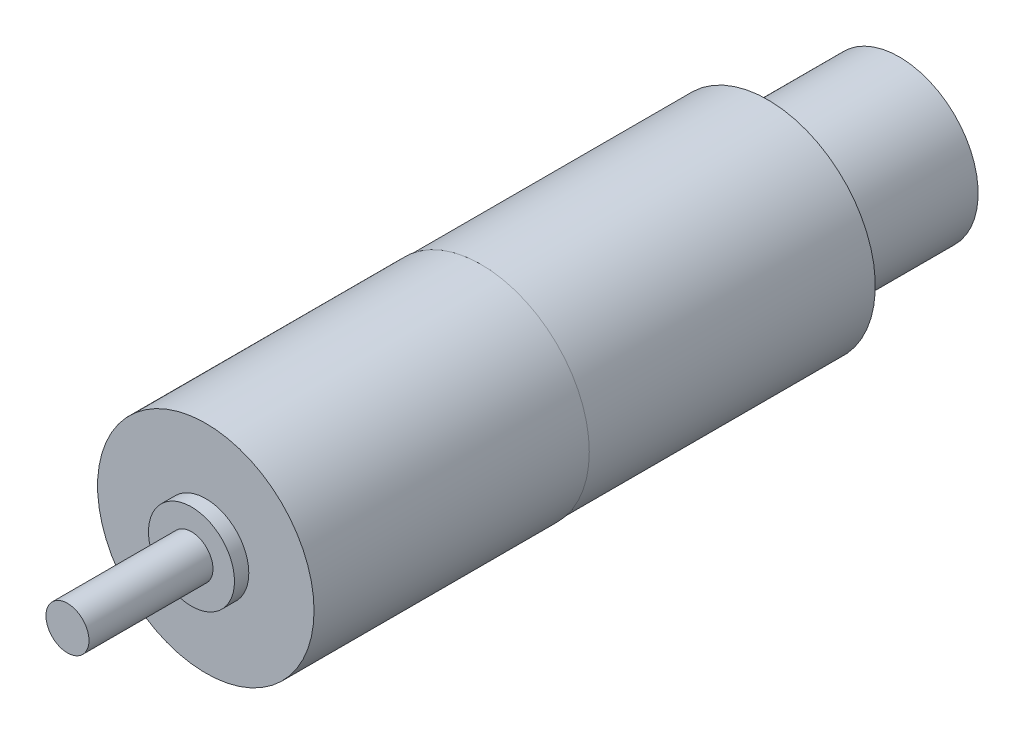
SolidWorks part; units mm, degrees
ref_plane "Front Plane" through (0, 0, 0) normal (0, 0, 1) x (1, 0, 0)
ref_plane "Top Plane" through (0, 0, 0) normal (0, 1, 0) x (1, 0, 0)
ref_plane "Right Plane" through (0, 0, 0) normal (1, 0, 0) x (0, 0, -1)
sketch "Sketch1" plane through (0, 0, 0) normal (0, 0, 1) x (1, 0, 0)
  circle A0 centre (0, 0) radius 15.1
extrude "Boss-Extrude1" add sketch "Sketch1" along normal blind 38.4 contours A0
sketch "Sketch2" plane through (0, 0, 0) normal (0, 0, -1) x (-1, 0, 0)
  circle A0 centre (0, 0) radius 15
extrude "Boss-Extrude2" add sketch "Sketch2" along normal blind 40 separate body
sketch "Sketch3" plane through (0, 0, 38.4) normal (0, 0, 1) x (1, 0, 0)
  circle A0 centre (0, 0) radius 6
extrude "Boss-Extrude3" add sketch "Sketch3" along normal blind 2 contours A0
sketch "Sketch4" plane through (0, 0, -40) normal (0, 0, -1) x (-1, 0, 0)
  circle A0 centre (0, 0) radius 11
extrude "Boss-Extrude4" add sketch "Sketch4" along normal blind 18.35 separate body contours A0
sketch "Sketch5" plane through (0, 0, 40.4) normal (0, 0, 1) x (1, 0, 0)
  circle A0 centre (0, 0) radius 3
extrude "Boss-Extrude5" add sketch "Sketch5" along normal blind 17.3 separate body contours A0
